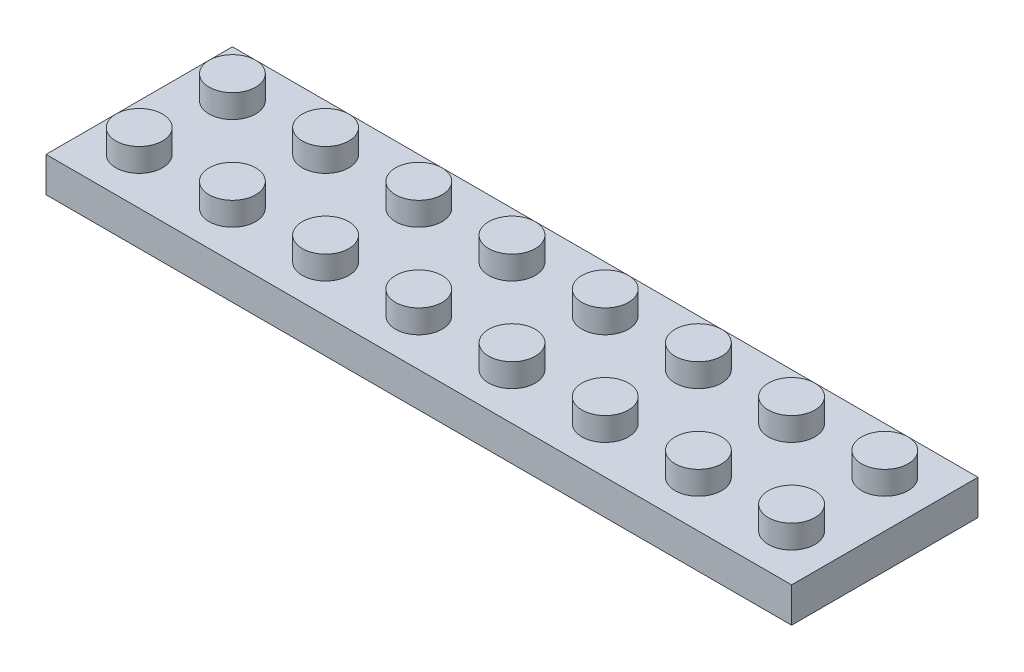
SolidWorks part; units mm, degrees
ref_plane "Front Plane" through (0, 0, 0) normal (0, 0, 1) x (1, 0, 0)
ref_plane "Top Plane" through (0, 0, 0) normal (0, 1, 0) x (1, 0, 0)
ref_plane "Right Plane" through (0, 0, 0) normal (1, 0, 0) x (0, 0, -1)
sketch "Sketch1" plane through (0, 0, 0) normal (0, 1, 0) x (1, 0, 0)
  line L1 (-32, 8) -> (32, 8)
  line L2 (-32, 8) -> (-32, -8)
  line L3 (-32, -8) -> (32, -8)
  line L4 (32, 8) -> (32, -8)
  line L5 (-32, 8) -> (32, -8) construction
  line L6 (-32, -8) -> (32, 8) construction
  point P0 (0, 0)
  dimension "D1" = 64
  dimension "D2" = 16
extrude "Boss-Extrude1" add sketch "Sketch1" along normal blind 3
sketch "Sketch2" plane through (0, 3, 0) normal (0, 1, 0) x (1, 0, 0)
  line L0 (-32, 8) -> (-32, -8) construction
  line L1 (32, 8) -> (-32, 8) construction
  circle A0 centre (-28, 4) radius 2
  circle A1 centre (-20, 4) radius 2
  circle A2 centre (-12, 4) radius 2
  circle A3 centre (-4, 4) radius 2
  circle A4 centre (4, 4) radius 2
  circle A5 centre (12, 4) radius 2
  circle A6 centre (20, 4) radius 2
  circle A7 centre (28, 4) radius 2
  circle A8 centre (-20, -4) radius 2
  circle A9 centre (-12, -4) radius 2
  circle A10 centre (-4, -4) radius 2
  circle A11 centre (4, -4) radius 2
  circle A12 centre (12, -4) radius 2
  circle A13 centre (20, -4) radius 2
  circle A14 centre (28, -4) radius 2
  circle A15 centre (-28, -4) radius 2
  dimension "D1" = 4
  dimension "D2" = 4
  dimension "D3" = 4
  dimension "D4" = 8
  dimension "D5" = 2
extrude "Boss-Extrude2" add sketch "Sketch2" along normal blind 2
shell "Shell2" thickness 1
sketch "Sketch3" plane through (0, 2, 0) normal (0, -1, 0) x (1, 0, 0)
  line L0 (-31, -7) -> (-31, 7) construction
  circle A0 centre (-23, 0) radius 2.8
  circle A1 centre (-23, 0) radius 1.8
  dimension "D1" = 5.6
  dimension "D2" = 3.6
  dimension "D3" = 8
extrude "Boss-Extrude3" add sketch "Sketch3" along normal blind 2
pattern_linear "LPattern1" count 7 spacing 8 along (1, 0, 0) of "Boss-Extrude3"
